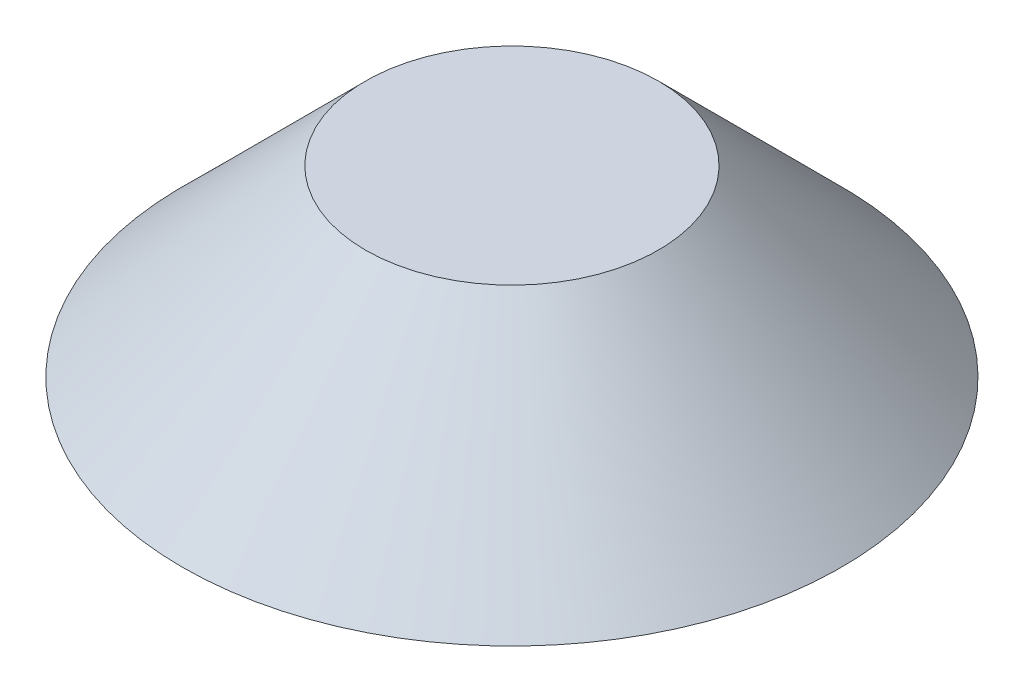
SolidWorks part; units mm, degrees
ref_plane "Front Plane" through (0, 0, 0) normal (0, 0, 1) x (1, 0, 0)
ref_plane "Top Plane" through (0, 0, 0) normal (0, 1, 0) x (1, 0, 0)
ref_plane "Right Plane" through (0, 0, 0) normal (1, 0, 0) x (0, 0, -1)
sketch "Sketch1" plane through (0, 0, 0) normal (0, 0, 1) x (1, 0, 0)
  line L0 (0, 141.5918) -> (0, -145.8105) construction
  line L1 (132, 0) -> (59.1213, 72.8787)
  line L2 (135, 0) -> (60, 75)
  line L3 (135, 0) -> (-16.4976, 0) construction
  line L4 (60, 75) -> (0, 75)
  line L5 (59.1213, 72.8787) -> (0, 72.8787)
  line L6 (135, 0) -> (132, 0)
  line L7 (0, 75) -> (0, 72.8787)
  line L9 (133.5, -1.5) -> (59.1213, 72.8787) construction
  dimension "D1" = 3
  dimension "D2" = 135
  dimension "D3" = 45
  dimension "D4" = 75
  dimension "D5" = 2.1213
revolve "Revolve1" add sketch "Sketch1" angle 360 about L0
sketch "Sketch2" plane through (0, 0, 0) normal (0, 1, 0) x (1, 0, 0)
  line L0 (-186.9146, 0) -> (201.9448, 0) construction
  line L1 (-121.5128, 5.2988) -> (-120.75, 6.3) construction
  line L5 (-120.75, -3.3) -> (-120.75, 3.3)
  line L6 (-131.751, -8.1388) -> (-125.55, 0) construction
  line L7 (-125.55, 0) -> (-120.75, -6.3) construction
  circle A0 centre (-125.55, 0) radius 1.8
  arc A3 (-120.75, -3.3) -> (-123.1462, -5.9469) centre (-123.41, -3.3) cw
  arc A6 (-131.5076, -11.3911) -> (-131.5076, 11.3911) centre (0, 0) cw
  arc A7 (-123.1462, -5.9469) -> (-131.5076, -11.3911) centre (-124.5703, -12.9026) ccw
  circle A10 centre (0, 0) radius 132 construction
  arc A11 (-123.1462, 5.9469) -> (-131.5076, 11.3911) centre (-124.5703, 12.9026) cw
  arc A12 (-120.75, 3.3) -> (-123.1462, 5.9469) centre (-123.41, 3.3) ccw
  point P3 (-125.55, 0)
  point P6 (-132, 0)
  point P9 (-120.75, 0)
  point P10 (-125.55, -1.8)
  point P25 (-123.75, 0)
  dimension "D1" = 3.6
  dimension "D3" = 6.6
  dimension "D4" = 7.1
  dimension "D2" = 11.25
  dimension "D6" = 2.66
  dimension "D7" = 7.1
  dimension "D5" = 3
extrude "Boss-Extrude1" add sketch "Sketch2" along normal blind 3
sketch "Sketch4" plane through (0, 0, 0) normal (0, 0, 1) x (1, 0, 0)
  line L0 (-120.75, 3) -> (-123.1462, 3) construction
  line L1 (-28.7574, 102) -> (-128.8995, 3) construction
  line L3 (-128.799, 3) -> (-129, 3) construction
  line L4 (-121.5977, 3) -> (-128.8995, 3)
  line L5 (-128.8995, 3) -> (-123.7068, 8.1335)
  arc A0 (-121.5977, 3) -> (-123.7068, 8.1335) centre (-121.5977, 6) cw
  dimension "D1" = 3
  dimension "D2" = 140.8171
extrude "Boss-Extrude2" add sketch "Sketch4" against normal blind 1.5 from offset 3.5 offset against normal yes
sketch "Sketch6" plane through (0, 0, -5) normal (0, 0, -1) x (-1, 0, 0)
  line L1 (128.8995, 3) -> (123.7068, 8.1335)
  line L4 (128.8995, 3) -> (123.7068, 8.1335)
  line L5 (121.5977, 3) -> (128.8995, 3)
  line L6 (121.5977, 3) -> (128.8995, 3)
  arc A1 (121.5977, 3) -> (123.7068, 8.1335) centre (121.5977, 6) ccw
  arc A2 (121.5977, 3) -> (123.7068, 8.1335) centre (121.5977, 6) ccw
  dimension "D1" = 0
mirror "Mirror1" about plane through (0, 0, 0) normal (0, 0, 1) of "Boss-Extrude2"
pattern_circular "CirPattern1" count 4 over 360 about axis through (0, 0, 0) along (0, 1, 0) of "Boss-Extrude1", "Boss-Extrude2", "Mirror1"
